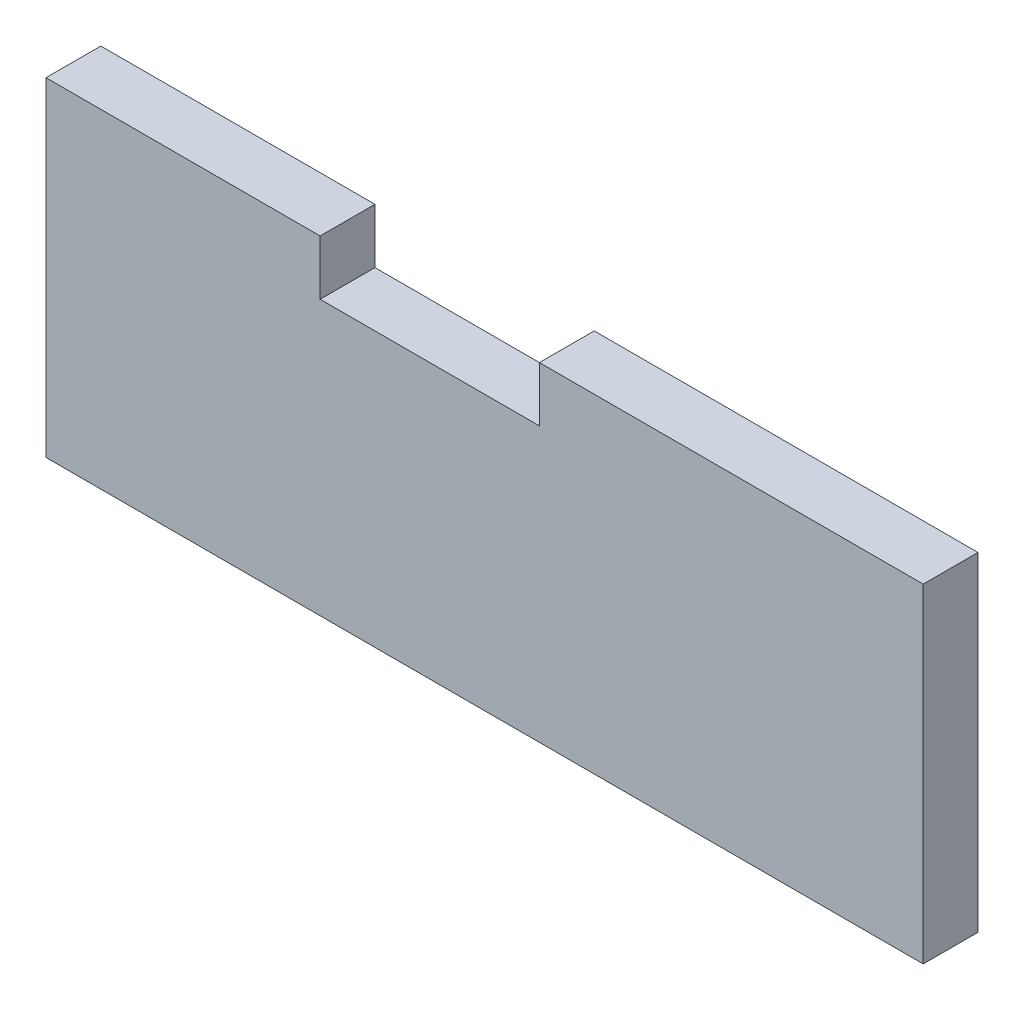
SolidWorks part; units mm, degrees
ref_plane "前视基准面" through (0, 0, 0) normal (0, 0, 1) x (1, 0, 0)
ref_plane "上视基准面" through (0, 0, 0) normal (0, 1, 0) x (1, 0, 0)
ref_plane "右视基准面" through (0, 0, 0) normal (1, 0, 0) x (0, 0, -1)
sketch "草图1" plane through (0, 0, 0) normal (0, 0, 1) x (1, 0, 0)
  line L1 (-40, -15) -> (40, -15)
  line L2 (-40, -15) -> (-40, 15)
  line L3 (-40, 15) -> (40, 15)
  line L4 (40, -15) -> (40, 15)
  line L5 (-40, -15) -> (40, 15) construction
  line L6 (-40, 15) -> (40, -15) construction
  point P0 (0, 0)
  dimension "D1" = 30
  dimension "D2" = 80
extrude "凸台-拉伸1" add sketch "草图1" along normal blind 5
sketch "草图2" plane through (0, 0, 0) normal (0, 0, -1) x (-1, 0, 0)
  line L0 (40, 15) -> (40, -15) construction
  line L1 (-5, 15) -> (15, 15)
  line L2 (-5, 15) -> (-5, 10)
  line L3 (-5, 10) -> (15, 10)
  line L4 (15, 15) -> (15, 10)
  line L5 (-40, 15) -> (40, 15) construction
  dimension "D1" = 20
  dimension "D2" = 5
  dimension "D3" = 25
extrude "切除-拉伸1" cut sketch "草图2" against normal blind 10
